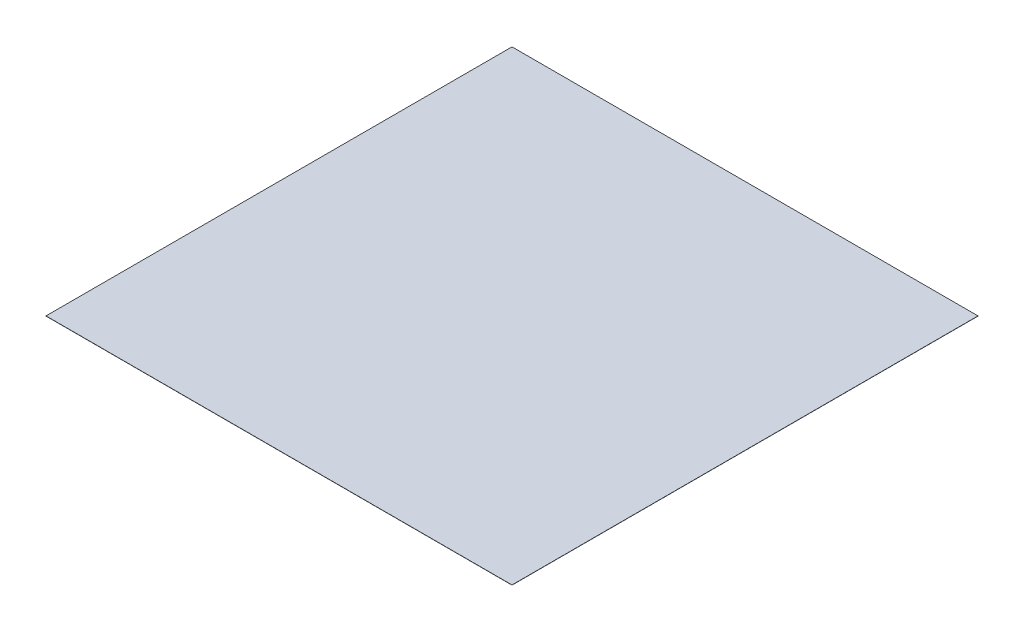
SolidWorks part; units mm, degrees
ref_plane "Front Plane" through (0, 0, 0) normal (0, 0, 1) x (1, 0, 0)
ref_plane "Top Plane" through (0, 0, 0) normal (0, 1, 0) x (1, 0, 0)
ref_plane "Right Plane" through (0, 0, 0) normal (1, 0, 0) x (0, 0, -1)
sketch "Sketch1" plane through (0, 0, 0) normal (0, 1, 0) x (1, 0, 0)
  line L1 (-2500, -2500) -> (2500, -2500)
  line L2 (-2500, -2500) -> (-2500, 2500)
  line L3 (-2500, 2500) -> (2500, 2500)
  line L4 (2500, -2500) -> (2500, 2500)
  line L5 (-2500, -2500) -> (2500, 2500) construction
  line L6 (-2500, 2500) -> (2500, -2500) construction
  point P0 (0, 0)
  dimension "D1" = 5000
extrude "Boss-Extrude1" add sketch "Sketch1" along normal blind 2
